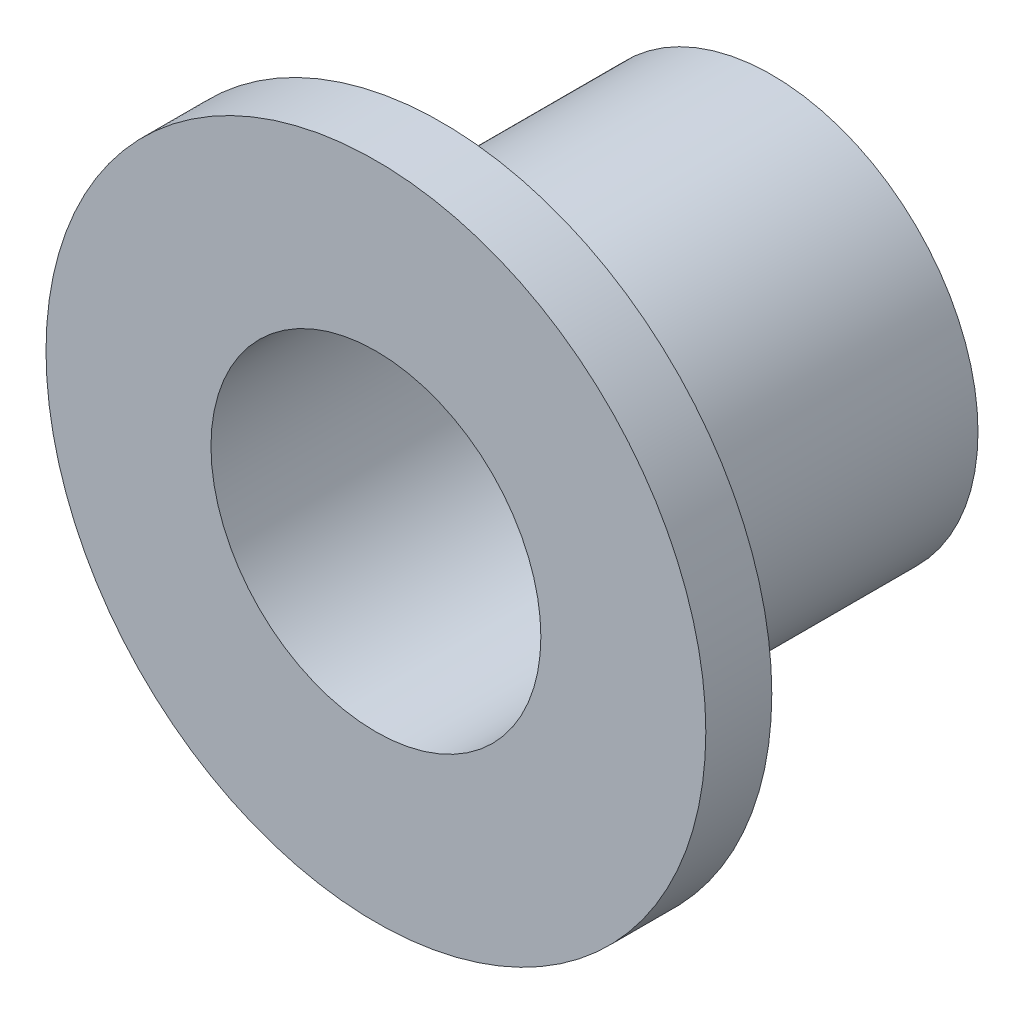
SolidWorks part; units mm, degrees
material "Delrin 2700 NC010, Low Viscosity Acetal Copolymer (SS)"
ref_plane "Front Plane" through (0, 0, 0) normal (0, 0, 1) x (1, 0, 0)
ref_plane "Top Plane" through (0, 0, 0) normal (0, 1, 0) x (1, 0, 0)
ref_plane "Right Plane" through (0, 0, 0) normal (1, 0, 0) x (0, 0, -1)
sketch "Sketch1" plane through (0, 0, 0) normal (0, 0, 1) x (1, 0, 0)
  circle A0 centre (0, 0) radius 3.175
  circle A1 centre (0, 0) radius 3.9688
  dimension "D1" = 6.35
  dimension "D2" = 7.9375
extrude "Boss-Extrude1" add sketch "Sketch1" along normal blind 6.35
sketch "Sketch2" plane through (0, 0, 6.35) normal (0, 0, 1) x (1, 0, 0)
  circle A0 centre (0, 0) radius 3.175
  circle A1 centre (0, 0) radius 6.35
  dimension "D1" = 12.7
extrude "Boss-Extrude2" add sketch "Sketch2" along normal blind 1.27
